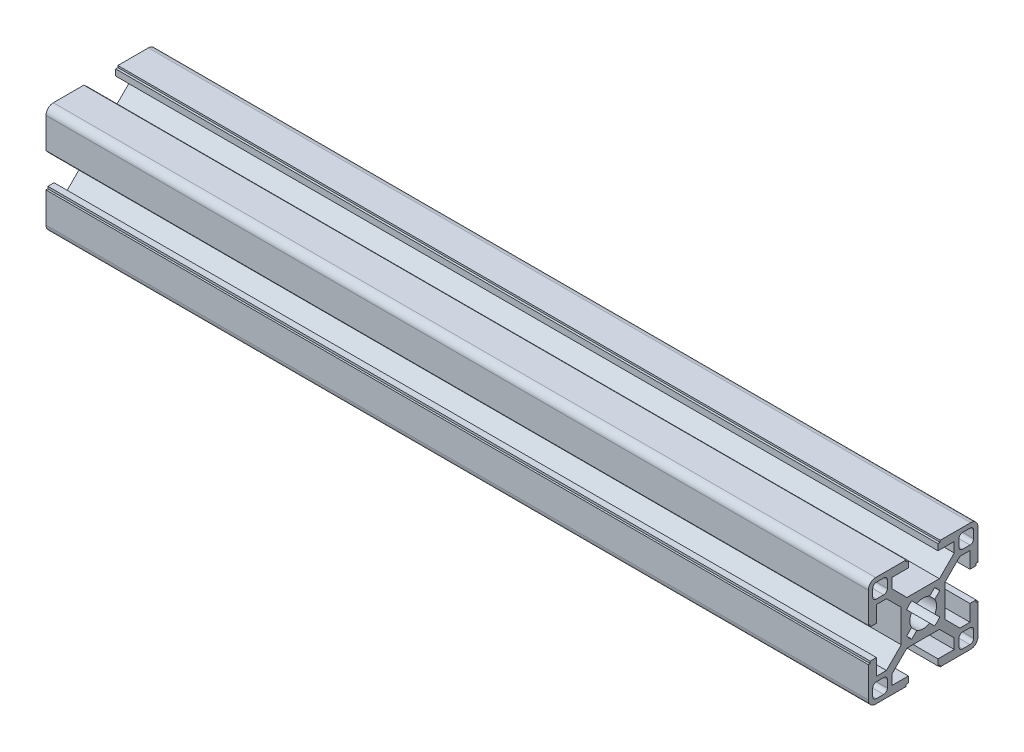
SolidWorks part; units mm, degrees
material "1060 Alloy"
ref_plane "Ebene vorne" through (0, 0, 0) normal (0, 0, 1) x (1, 0, 0)
ref_plane "Ebene oben" through (0, 0, 0) normal (0, 1, 0) x (1, 0, 0)
ref_plane "Ebene rechts" through (0, 0, 0) normal (1, 0, 0) x (0, 0, -1)
sketch "Skizze1" plane through (0, 0, 0) normal (1, 0, 0) x (0, 0, -1)
  line L0 (8.5, 10.0556) -> (4.4444, 6)
  line L1 (13, 15) -> (-13, 15)
  line L2 (15, 13) -> (15, -13)
  line L3 (13, -15) -> (-13, -15)
  line L4 (-15, 13) -> (-15, -13)
  line L5 (15, 15) -> (-15, -15) construction
  line L6 (15, -15) -> (-15, 15) construction
  line L7 (6, 6) -> (-6, 6)
  line L8 (6, 6) -> (6, -6)
  line L9 (6, -6) -> (-6, -6)
  line L10 (-6, 6) -> (-6, -6)
  line L11 (6, 6) -> (-6, -6) construction
  line L12 (6, -6) -> (-6, 6) construction
  line L13 (8.5, 12.8) -> (-8.5, 12.8)
  line L14 (8.5, 12.8) -> (8.5, 6)
  line L15 (8.5, 6) -> (-8.5, 6)
  line L16 (-8.5, 12.8) -> (-8.5, 6)
  line L17 (4.05, 15) -> (-4.05, 15)
  line L18 (4.05, 15) -> (4.05, 12.8)
  line L19 (4.05, 12.8) -> (-4.05, 12.8)
  line L20 (-4.05, 15) -> (-4.05, 12.8)
  line L21 (-8.5, 10.0556) -> (-4.4444, 6)
  line L22 (3.1172, 4.5314) -> (1.7751, 3.1893)
  line L23 (-3.1172, 4.5314) -> (-1.7751, 3.1893)
  line L24 (15, -4.05) -> (12.8, -4.05)
  line L25 (4.05, 15) -> (4.6516, 15)
  line L26 (4.05, 15) -> (4.05, 14.5)
  line L27 (4.05, 14.5) -> (4.6516, 14.5)
  line L28 (4.6516, 15) -> (4.6516, 14.5)
  line L29 (-4.05, 15) -> (-4.6516, 15)
  line L30 (-4.05, 15) -> (-4.05, 14.5)
  line L31 (-4.05, 14.5) -> (-4.6516, 14.5)
  line L32 (-4.6516, 15) -> (-4.6516, 14.5)
  line L33 (15, -4.6516) -> (14.5, -4.6516)
  line L34 (14.5, -4.05) -> (14.5, -4.6516)
  line L35 (14.5, 4.05) -> (14.5, 4.6516)
  line L36 (15, 4.6516) -> (14.5, 4.6516)
  line L37 (15, 4.05) -> (12.8, 4.05)
  line L38 (12.8, 8.5) -> (6, 8.5)
  line L39 (12.8, -8.5) -> (12.8, 8.5)
  line L40 (12.8, -8.5) -> (6, -8.5)
  line L41 (10.0556, -8.5) -> (6, -4.4444)
  line L42 (10.0556, 8.5) -> (6, 4.4444)
  line L43 (4.5314, -3.1172) -> (3.1893, -1.7751)
  line L44 (4.5314, 3.1172) -> (3.1893, 1.7751)
  line L45 (-4.05, -15) -> (-4.05, -12.8)
  line L46 (-4.6516, -15) -> (-4.6516, -14.5)
  line L47 (-4.05, -14.5) -> (-4.6516, -14.5)
  line L48 (4.05, -14.5) -> (4.6516, -14.5)
  line L49 (4.6516, -15) -> (4.6516, -14.5)
  line L50 (4.05, -15) -> (4.05, -12.8)
  line L51 (8.5, -12.8) -> (8.5, -6)
  line L52 (-8.5, -12.8) -> (8.5, -12.8)
  line L53 (-8.5, -12.8) -> (-8.5, -6)
  line L54 (-8.5, -10.0556) -> (-4.4444, -6)
  line L55 (8.5, -10.0556) -> (4.4444, -6)
  line L56 (-3.1172, -4.5314) -> (-1.7751, -3.1893)
  line L57 (3.1172, -4.5314) -> (1.7751, -3.1893)
  line L58 (-15, 4.05) -> (-12.8, 4.05)
  line L59 (-15, 4.6516) -> (-14.5, 4.6516)
  line L60 (-14.5, 4.05) -> (-14.5, 4.6516)
  line L61 (-14.5, -4.05) -> (-14.5, -4.6516)
  line L62 (-15, -4.6516) -> (-14.5, -4.6516)
  line L63 (-15, -4.05) -> (-12.8, -4.05)
  line L64 (-12.8, -8.5) -> (-6, -8.5)
  line L65 (-12.8, 8.5) -> (-12.8, -8.5)
  line L66 (-12.8, 8.5) -> (-6, 8.5)
  line L67 (-10.0556, 8.5) -> (-6, 4.4444)
  line L68 (-10.0556, -8.5) -> (-6, -4.4444)
  line L69 (-4.5314, 3.1172) -> (-3.1893, 1.7751)
  line L70 (-4.5314, -3.1172) -> (-3.1893, -1.7751)
  line L71 (6, -8.5) -> (6, 8.5)
  line L72 (-8.5, -6) -> (8.5, -6)
  line L73 (-6, 8.5) -> (-6, -8.5)
  line L75 (12.8, 13.8) -> (10.8, 13.8)
  line L76 (13.8, 12.8) -> (13.8, 10.8)
  line L77 (12.8, 9.8) -> (10.8, 9.8)
  line L78 (9.8, 12.8) -> (9.8, 10.8)
  line L79 (13.8, 13.8) -> (9.8, 9.8) construction
  line L80 (13.8, 9.8) -> (9.8, 13.8) construction
  line L81 (-10.8, 13.8) -> (-12.8, 13.8)
  line L82 (-9.8, 12.8) -> (-9.8, 10.8)
  line L83 (-10.8, 9.8) -> (-12.8, 9.8)
  line L84 (-13.8, 12.8) -> (-13.8, 10.8)
  line L85 (-9.8, 13.8) -> (-13.8, 9.8) construction
  line L86 (-9.8, 9.8) -> (-13.8, 13.8) construction
  line L87 (12.8, -9.8) -> (10.8, -9.8)
  line L88 (13.8, -10.8) -> (13.8, -12.8)
  line L89 (12.8, -13.8) -> (10.8, -13.8)
  line L90 (9.8, -10.8) -> (9.8, -12.8)
  line L91 (13.8, -9.8) -> (9.8, -13.8) construction
  line L92 (13.8, -13.8) -> (9.8, -9.8) construction
  line L93 (-10.8, -9.8) -> (-12.8, -9.8)
  line L94 (-9.8, -10.8) -> (-9.8, -12.8)
  line L95 (-10.8, -13.8) -> (-12.8, -13.8)
  line L96 (-13.8, -10.8) -> (-13.8, -12.8)
  line L97 (-9.8, -9.8) -> (-13.8, -13.8) construction
  line L98 (-9.8, -13.8) -> (-13.8, -9.8) construction
  arc A0 (13, -15) -> (15, -13) centre (13, -13) ccw
  arc A1 (-13, -15) -> (-15, -13) centre (-13, -13) cw
  arc A2 (-15, 13) -> (-13, 15) centre (-13, 13) cw
  arc A3 (13, 15) -> (15, 13) centre (13, 13) cw
  circle A4 centre (0, 0) radius 3.65
  circle A5 centre (0, 0) radius 5.5
  circle A6 centre (0, 0) radius 3.65
  circle A7 centre (0, 0) radius 3.65
  circle A8 centre (0, 0) radius 3.65
  arc A9 (12.8, -13.8) -> (13.8, -12.8) centre (12.8, -12.8) ccw
  arc A10 (13.8, -10.8) -> (12.8, -9.8) centre (12.8, -10.8) ccw
  arc A11 (9.8, -12.8) -> (10.8, -13.8) centre (10.8, -12.8) ccw
  arc A12 (9.8, -10.8) -> (10.8, -9.8) centre (10.8, -10.8) cw
  arc A13 (-10.8, -13.8) -> (-9.8, -12.8) centre (-10.8, -12.8) ccw
  arc A14 (-10.8, -9.8) -> (-9.8, -10.8) centre (-10.8, -10.8) cw
  arc A15 (-13.8, -12.8) -> (-12.8, -13.8) centre (-12.8, -12.8) ccw
  arc A16 (-13.8, -10.8) -> (-12.8, -9.8) centre (-12.8, -10.8) cw
  arc A17 (-12.8, 9.8) -> (-13.8, 10.8) centre (-12.8, 10.8) cw
  arc A18 (-10.8, 9.8) -> (-9.8, 10.8) centre (-10.8, 10.8) ccw
  arc A19 (-13.8, 12.8) -> (-12.8, 13.8) centre (-12.8, 12.8) cw
  arc A20 (-10.8, 13.8) -> (-9.8, 12.8) centre (-10.8, 12.8) cw
  arc A21 (13.8, 10.8) -> (12.8, 9.8) centre (12.8, 10.8) cw
  arc A22 (10.8, 9.8) -> (9.8, 10.8) centre (10.8, 10.8) cw
  arc A23 (10.8, 13.8) -> (9.8, 12.8) centre (10.8, 12.8) ccw
  arc A24 (12.8, 13.8) -> (13.8, 12.8) centre (12.8, 12.8) cw
  point P0 (0, 0)
  point P33 (0, 12.8)
  point P34 (0, 15)
  point P36 (0, 12.8)
  point P50 (11.8, 11.8)
  point P122 (0, 0)
  point P125 (-11.8, 11.8)
  point P129 (0, 0)
  point P131 (11.8, -11.8)
  point P136 (-11.8, -11.8)
  dimension "D2" = 2
  dimension "D3" = 7.3
  dimension "D4" = 11
  dimension "D20" = 1
  dimension "D1" = 30
  dimension "D5" = 12
  dimension "D6" = 17
  dimension "D7" = 8.1
  dimension "D8" = 2.2
  dimension "D9" = 9
  dimension "D10" = 1.1
  dimension "D11" = 1.1
  dimension "D12" = 1
  dimension "D13" = 1
  dimension "D14" = 0.5
  dimension "D15" = 0.6016
  dimension "D18" = 4
  dimension "D19" = 1.2
  dimension "D16" = 4
  dimension "D17" = 4
extrude "Aufsatz-Linear austragen1" add sketch "Skizze1" along normal blind 300 contours A3 L1 L28 L27 L18 L13 L14 L38 L39 L37 L35 L36 L2 | L42 L38 L14 | L71 L15 L42 L14 L38 L0 | L42 L15 L8 | L7 L71 L0 | L38 L14 L0 | L7 L15 L10 L9 L8 A5 | L43 A5 L44 A4 | L22 A5 L23 A4 | L69 A5 L70 A4 | L56 A5 L57 A4 | L3 A0 L2 L33 L34 L24 L39 L40 L51 L52 L50 L48 L49 | L51 L40 L41 | L72 L71 L55 L40 L51 L41 | L8 L72 L41 | L55 L71 L9 | L55 L51 L40 | L73 L72 L68 L53 L64 L54 | L68 L72 L10 | L9 L73 L54 | L68 L64 L53 | L64 L53 L54 | A1 L3 L46 L47 L45 L52 L53 L64 L65 L63 L61 L62 L4 | A2 L4 L59 L60 L58 L65 L66 L16 L13 L20 L31 L32 L1 | L66 L67 L16 | L16 L66 L21 | L73 L21 L66 L16 L67 L15 | L21 L73 L15 | L15 L67 L10
scale "Scale1" scale about centroid uniform scaling no x scale factor 1 y scale factor 1.333333 z scale factor 1.333333
